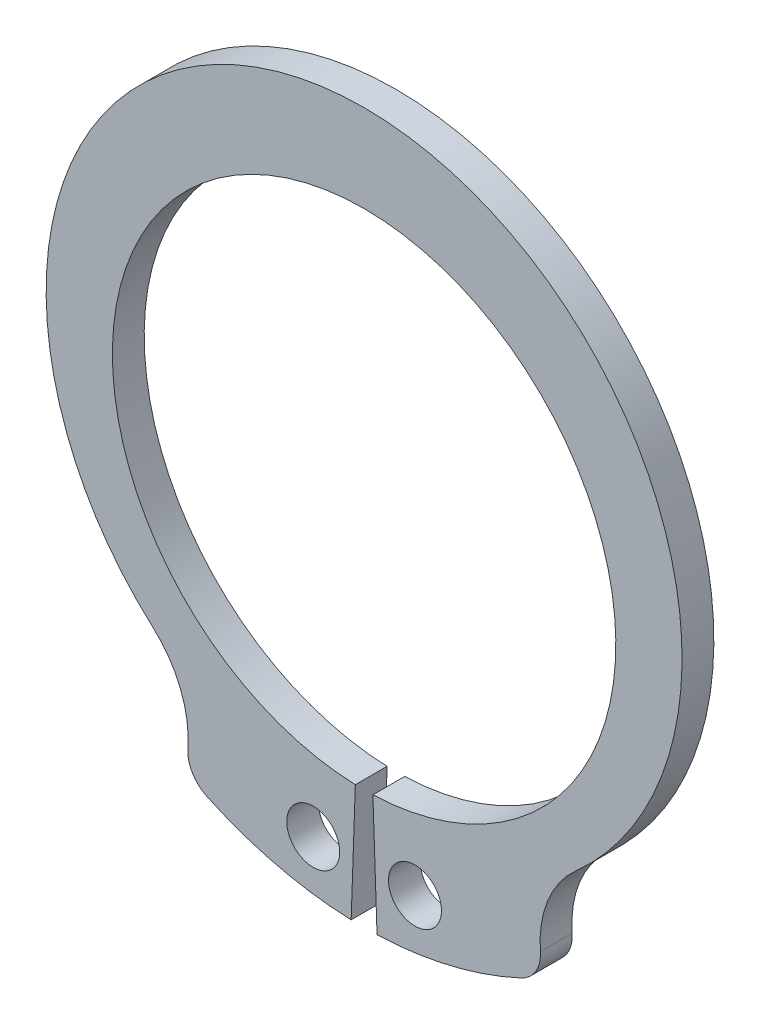
SolidWorks part; units mm, degrees
ref_plane "Front Plane" through (0, 0, 0) normal (0, 0, 1) x (1, 0, 0)
ref_plane "Top Plane" through (0, 0, 0) normal (0, 1, 0) x (1, 0, 0)
ref_plane "Right Plane" through (0, 0, 0) normal (1, 0, 0) x (0, 0, -1)
sketch "Sketch2" plane through (0, 0, 0) normal (0, 0, 1) x (1, 0, 0)
  line L0 (0, 0) -> (0, -23.75) construction
  line L1 (0, 0) -> (6.5464, -22.83)
  line L2 (0, 0) -> (-6.5464, -22.83)
  circle A0 centre (0, 0) radius 23.75
  circle A1 centre (0, -1.4) radius 20.75
  circle A6 centre (-7.7551, -17.9755) radius 2.5
  circle A7 centre (-11.896, -11.7222) radius 5
  circle A9 centre (0, -1.4) radius 15.8
  circle A10 centre (-7.7551, -17.9755) radius 1
  circle A11 centre (7.7551, -17.9755) radius 1
  circle A12 centre (7.7551, -17.9755) radius 2.5
  circle A13 centre (11.896, -11.7222) radius 5
  dimension "D1" = 47.5
  dimension "D5" = 41.5
  dimension "D2" = 10
  dimension "D6" = 5
  dimension "D7" = 31.6
  dimension "D8" = 2
  dimension "D3" = 32
  dimension "D4" = 1.4
sketch "Sketch3" plane through (0, 0, 0) normal (0, 0, 1) x (1, 0, 0)
  line L0 (0, 0) -> (0, -16.3969) construction
  line L1 (0, 0) -> (0.4886, -13.9915)
  line L2 (0, 0) -> (-0.4886, -13.9915)
  circle A0 centre (0, 0) radius 9.5
  circle A1 centre (0, 0) radius 14
  circle A2 centre (0, 0.8) radius 12
  circle A3 centre (10.6411, -11.1485) radius 4
  circle A4 centre (5.4063, -11.5471) radius 1.25
  circle A5 centre (1.9197, -11.9915) radius 1
  circle A6 centre (-10.6411, -11.1485) radius 4
  circle A7 centre (-5.4063, -11.5471) radius 1.25
  circle A8 centre (-1.9197, -11.9915) radius 1
  dimension "D1" = 19
  dimension "D2" = 24
  dimension "D3" = 0.8
  dimension "D4" = 28
  dimension "D7" = 2.5
  dimension "D8" = 8
  dimension "D11" = 2
  dimension "D5" = 2
  dimension "D6" = 5
  dimension "D9" = 1.5
  dimension "D10" = 2
extrude "Boss-Extrude1" add sketch "Sketch3" along normal blind 1.2 contours A2 A8 L2 A0 L1 A5 | A2 A8 A6 A7 A1 L2 | A7 | A5 A2 L1 A1 A4 A3 | A4
equation "\"D1@Sketch2\" = \"G_anneau_alesage_rouleau\""
equation "\"c_anneau\"=31.6"
equation "\"D5@Sketch2\" = \"G_anneau_alesage_rouleau\" - 6"
equation "\"e_anneau\"=1.75"
equation "\"D2@Sketch2\"=2*\"D6@Sketch2\""
equation "\"D7@Sketch2\"=\"c_anneau\""
equation "\"d_ext_rouleau\"= 90"
equation "\"epaisseur_rouleau\"=80"
equation "\"alesage-rouleau\"= 52"
equation "\"jeu_dent_rouleau\"= 2"
equation "\"profondeur_dent_rouleau\"=4"
equation "\"n_dent_roueau\"= 15"
equation "\"d_ext_roulement_rouleau\"= 42"
equation "\"d_int_roulement_rouleau\"= 20"
equation "\"B_roulement_rouleau\"= 12"
equation "\"r_roulement_rouleau\"= 0.6"
equation "\"d_bille_roulement_rouleau\"= 8"
equation "\"F_anneau_alesage_rouleau\"=1.85"
equation "\"G_anneau_alesage_rouleau\"=47.5"
equation "\"K_anneau_alesage_rouleau\"=3.75"
equation "\"d_vis_flasque_rouleau\"=5"
equation "\"l-x_vis_flasque_rouleau\"=4"
equation "\"g_anneau_arbre_rouleau\"=19"
equation "\"f_anneau_arbre_rouleau\"=1.3"
equation "\"k_anneau_arbre_rouleau\"=1.5"
equation "\"h_matrice\"= 18"
equation "\"d_matrice\"= 220"
equation "\"d_granulat\"= 8"
equation "\"zone_vide_matrice\" = 48"
equation "\"d_alesage_matrice\"=20"
equation "\"a_clavette_alesage_matrice\"=6"
equation "\"entrax_vis_rouleau\"=65"
